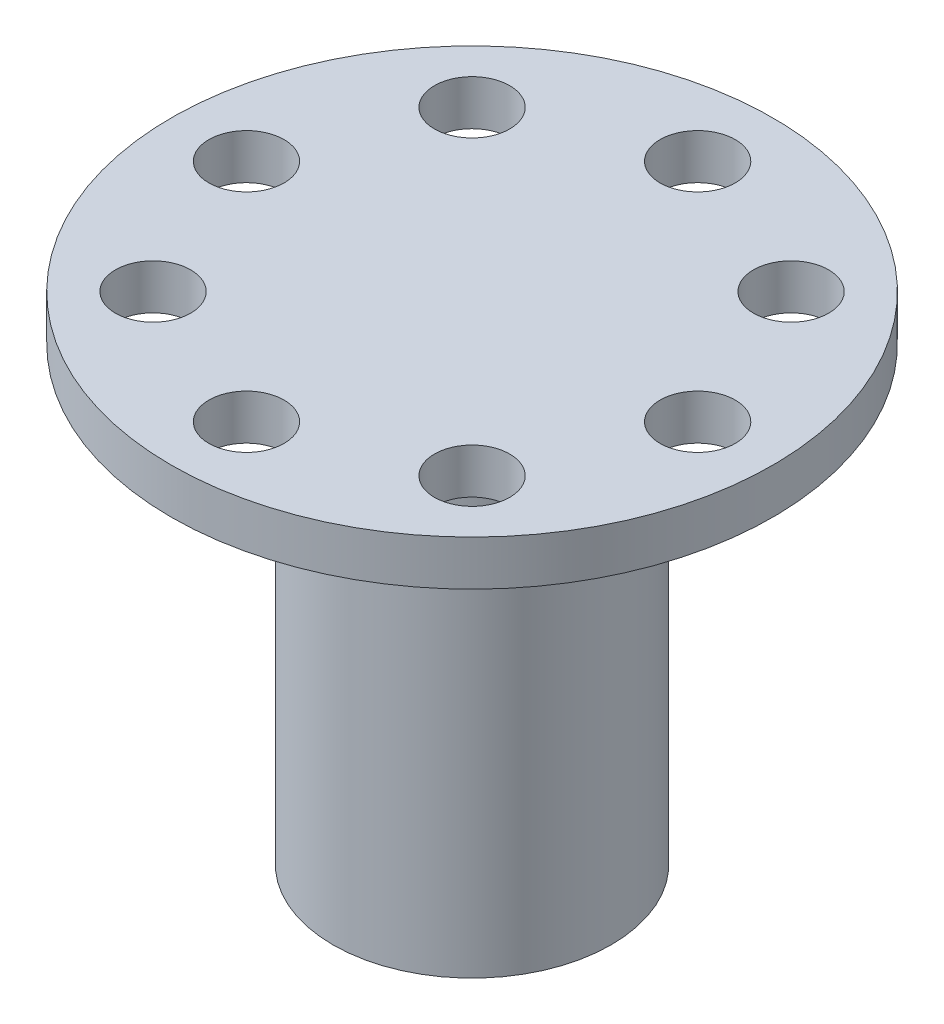
SolidWorks part; units mm, degrees
ref_plane "Front Plane" through (0, 0, 0) normal (0, 0, 1) x (1, 0, 0)
ref_plane "Top Plane" through (0, 0, 0) normal (0, 1, 0) x (1, 0, 0)
ref_plane "Right Plane" through (0, 0, 0) normal (1, 0, 0) x (0, 0, -1)
sketch "Sketch1" plane through (0, 0, 0) normal (0, 1, 0) x (1, 0, 0)
  circle A0 centre (0, 0) radius 10
  circle A1 centre (0, 0) radius 20
  dimension "D1" = 20
  dimension "D2" = 40
extrude "Boss-Extrude1" add sketch "Sketch1" along normal blind 3 contours A1 A0 | A0
sketch "Sketch2" plane through (0, 3, 0) normal (0, 1, 0) x (1, 0, 0)
  circle A0 centre (0, 0) radius 15
  circle A1 centre (0, 15) radius 2.5
  circle A2 centre (0, 0) radius 15
  circle A3 centre (10.6066, 10.6066) radius 2.5
  circle A4 centre (0, 0) radius 15
  circle A5 centre (15, 0) radius 2.5
  circle A6 centre (0, 0) radius 15
  circle A7 centre (10.6066, -10.6066) radius 2.5
  circle A8 centre (0, 0) radius 15
  circle A9 centre (0, -15) radius 2.5
  circle A10 centre (0, 0) radius 15
  circle A11 centre (-10.6066, -10.6066) radius 2.5
  circle A12 centre (0, 0) radius 15
  circle A13 centre (-15, 0) radius 2.5
  circle A14 centre (0, 0) radius 15
  circle A15 centre (-10.6066, 10.6066) radius 2.5
  point P6 (3.06, 3.3378)
  point P7 (0, 0)
  point P28 (0, 0)
  point P30 (0, 0)
  dimension "D1" = 30
  dimension "D2" = 5
  dimension "D3" = 8
extrude "Cut-Extrude1" cut sketch "Sketch2" against normal blind 3 contours A14 A15 | A0 A1 | A2 A3 | A2 A3 | A4 A5 | A4 A5 | A6 A7 | A6 A7 | A8 A9 | A8 A9 | A10 A11 | A10 A11 | A12 A13 | A12 A13 | A14 A15 | A0 A1
sketch "Sketch3" plane through (0, 0, 0) normal (0, -1, 0) x (1, 0, 0)
  circle A0 centre (0, 0) radius 9.25
  circle A1 centre (0, 0) radius 7.25
  dimension "D1" = 18.5
  dimension "D2" = 2
extrude "Boss-Extrude2" add sketch "Sketch3" along normal blind 30
